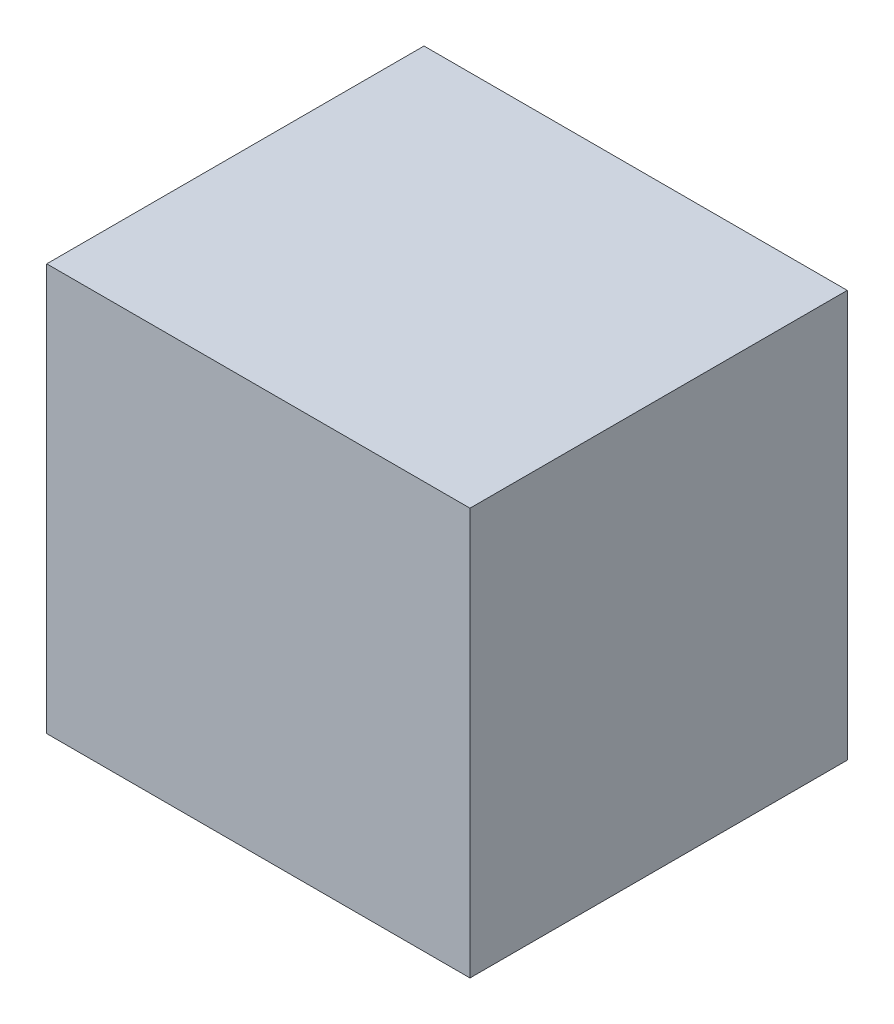
SolidWorks part; units mm, degrees
ref_plane "Front Plane" through (0, 0, 0) normal (0, 0, 1) x (1, 0, 0)
ref_plane "Top Plane" through (0, 0, 0) normal (0, 1, 0) x (1, 0, 0)
ref_plane "Right Plane" through (0, 0, 0) normal (1, 0, 0) x (0, 0, -1)
sketch "Sketch1" plane through (0, 0, 0) normal (1, 0, 0) x (0, 0, -1)
  line L1 (-1.573, 19.7941) -> (25.1687, 19.7941)
  line L2 (-1.573, 19.7941) -> (-1.573, -9.045)
  line L3 (-1.573, -9.045) -> (25.1687, -9.045)
  line L4 (25.1687, 19.7941) -> (25.1687, -9.045)
extrude "Boss-Extrude1" add sketch "Sketch1" along normal blind 30
scale "Scale1" scale about centroid uniform scaling yes scale factor 3
